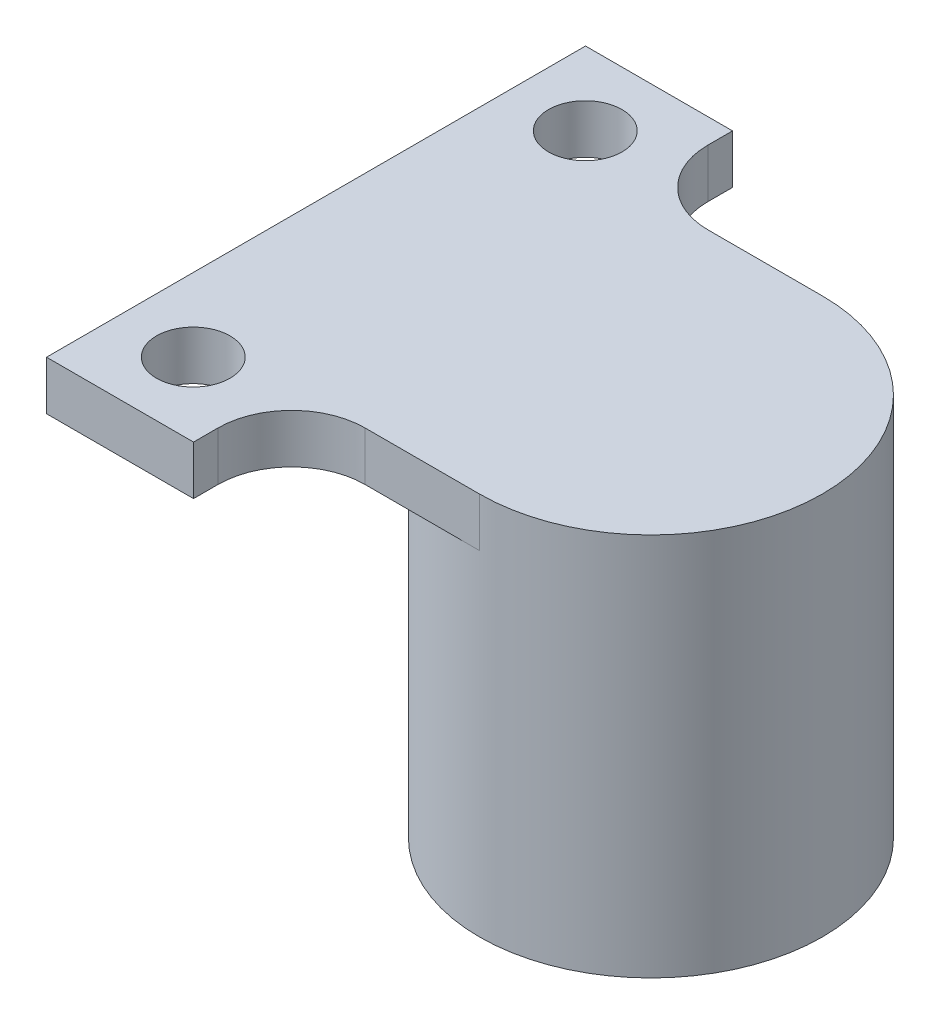
SolidWorks part; units mm, degrees
material "Copper"
ref_plane "Front Plane" through (0, 0, 0) normal (0, 0, 1) x (1, 0, 0)
ref_plane "Top Plane" through (0, 0, 0) normal (0, 1, 0) x (1, 0, 0)
ref_plane "Right Plane" through (0, 0, 0) normal (1, 0, 0) x (0, 0, -1)
sketch "Sketch1" plane through (0, 0, 0) normal (0, 1, 0) x (1, 0, 0)
  circle A0 centre (0, 0) radius 5.2
  circle A1 centre (0, 0) radius 7
  dimension "D1" = 10.4
  dimension "D2" = 14
extrude "Boss-Extrude1" add sketch "Sketch1" along normal blind 15.66
sketch "Sketch2" plane through (0, 15.66, 0) normal (0, 1, 0) x (1, 0, 0)
  line L0 (0, 0) -> (-6.5789, 0) construction
  line L1 (0, 5.2) -> (0, 7)
  line L2 (-13.67, -7) -> (0, -7)
  line L3 (-13.67, -7) -> (-13.67, 7)
  line L4 (-13.67, 7) -> (0, 7)
  line L5 (0, -7) -> (0, -5.2)
  line L6 (-13.67, -7) -> (0, 7) construction
  line L7 (-13.67, 7) -> (0, -7) construction
  line L8 (-7.67, 7) -> (-7.67, 11)
  line L9 (-13.67, -7) -> (-7.67, -7)
  line L10 (-13.67, -7) -> (-13.67, -11)
  line L11 (-13.67, -11) -> (-7.67, -11)
  line L12 (-7.67, -7) -> (-7.67, -11)
  line L13 (-13.67, 11) -> (-7.67, 11)
  line L14 (-13.67, 7) -> (-13.67, 11)
  line L15 (-13.67, 7) -> (-7.67, 7)
  circle A0 centre (0, 0) radius 7 construction
  circle A1 centre (0, 0) radius 5.2 construction
  arc A2 (0, 5.2) -> (0, -5.2) centre (0, 0) ccw
  point P3 (-6.835, 0)
  circle M6 centre (0, 0) radius 7
  dimension "D1" = 4
  dimension "D2" = 13.67
  dimension "D3" = 6
extrude "Boss-Extrude2" add sketch "Sketch2" against normal blind 2 contours L12 L2 L10 L11 | L4 L3 L2 M6 | L15 L8 L13 L14
sketch "Sketch4" plane through (0, 13.66, 0) normal (0, -1, 0) x (1, 0, 0)
  line L0 (-13.67, 8) -> (-7.899, 8) construction
  line L2 (-13.67, -11) -> (-13.67, 11) construction
  line L3 (0, 0) -> (-21.2142, 0) construction
  line L4 (-13.67, 11) -> (-7.67, 11) construction
  circle A0 centre (-10.68, 8) radius 1.5
  circle A1 centre (-10.68, -8) radius 1.5
  dimension "D1" = 3
  dimension "D2" = 2.99
  dimension "D3" = 3
extrude "Cut-Extrude1" cut sketch "Sketch4" against normal blind 10 contours A1 | A0
fillet "Fillet1" radius 3 2 edges at (-7.67, 14.66, 7) (-7.67, 14.66, -7)
sketch "Sketch5" plane through (0, 15.66, 0) normal (0, 1, 0) x (1, 0, 0)
  circle A0 centre (0, 0) radius 5.2 construction
  circle A1 centre (0, 0) radius 5.2
extrude "Boss-Extrude3" add sketch "Sketch5" against normal blind 1
